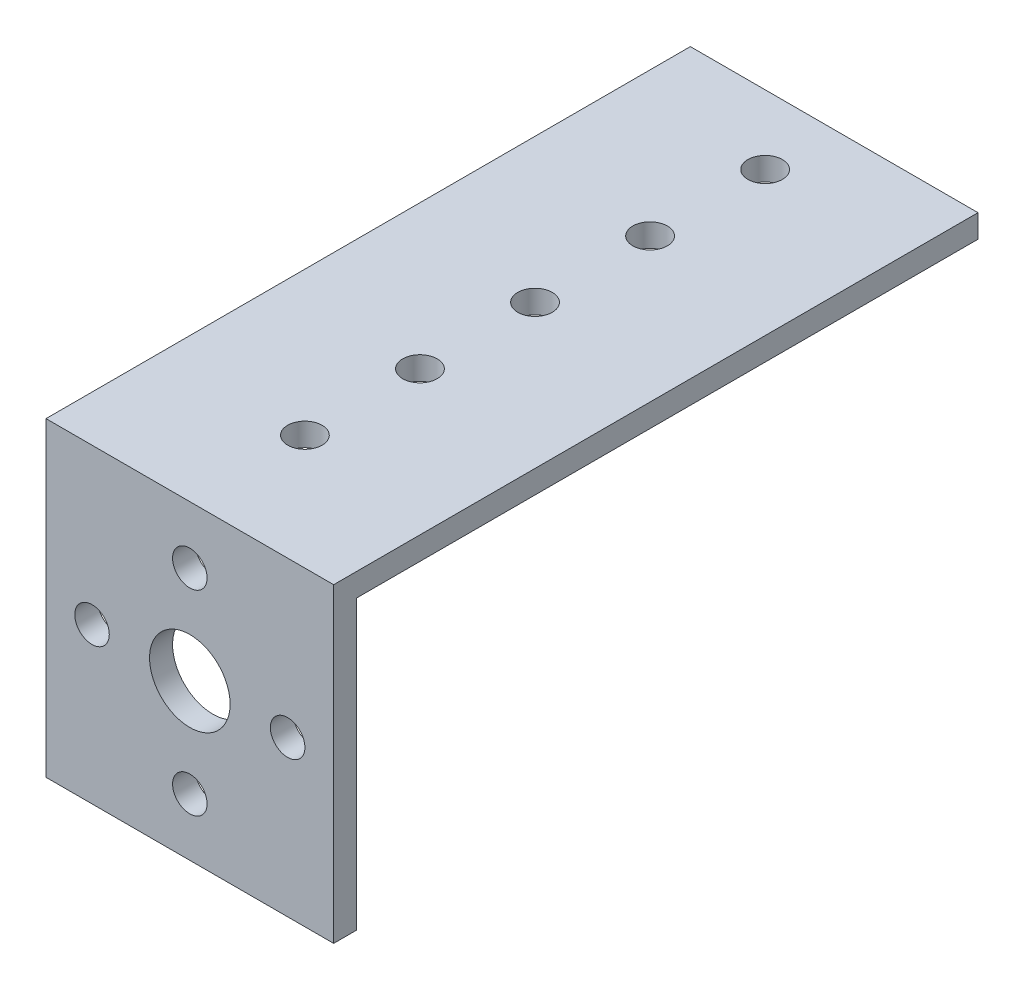
SolidWorks part; units mm, degrees
ref_plane "Front Plane" through (0, 0, 0) normal (0, 0, 1) x (1, 0, 0)
ref_plane "Top Plane" through (0, 0, 0) normal (0, 1, 0) x (1, 0, 0)
ref_plane "Right Plane" through (0, 0, 0) normal (1, 0, 0) x (0, 0, -1)
sketch "Sketch1" plane through (0, 0, 0) normal (1, 0, 0) x (0, 0, -1)
  line L0 (0, 0) -> (0, 27)
  line L1 (0, 27) -> (56, 27)
  line L2 (56, 27) -> (56, 25)
  line L3 (56, 25) -> (2, 25)
  line L4 (2, 25) -> (2, 0)
  line L5 (2, 0) -> (0, 0)
  dimension "D1" = 25
  dimension "D2" = 2
  dimension "D3" = 54
extrude "Boss-Extrude1" add sketch "Sketch1" along normal blind 25
sketch "Sketch2" plane through (0, 0, 0) normal (0, 0, 1) x (1, 0, 0)
  line L0 (12.5, 27) -> (12.5, 0) construction
  line L1 (25, 13.5) -> (0, 13.5) construction
  line L4 (0, 27) -> (0, 0)
  line L5 (0, 0) -> (25, 0)
  line L6 (25, 0) -> (25, 27)
  line L7 (25, 27) -> (0, 27)
  line L8 (0, 27) -> (0, 0) construction
  line L9 (0, 0) -> (25, 0) construction
  line L10 (25, 0) -> (25, 27) construction
  line L11 (25, 27) -> (0, 27) construction
  circle A3 centre (4, 13.5) radius 1.5
  circle A4 centre (12.5, 13.5) radius 3.5
  circle A5 centre (12.5, 22) radius 1.5
  circle A6 centre (21, 13.5) radius 1.5
  circle A7 centre (12.5, 5) radius 1.5
  point P21 (12.5, 13.5)
  dimension "D2" = 3
  dimension "D3" = 7
  dimension "D4" = 8.5
  dimension "D1" = 0
  dimension "D5" = 4
extrude "Cut-Extrude1" cut sketch "Sketch2" against normal blind 25
sketch "Sketch3" plane through (0, 27, 0) normal (0, 1, 0) x (1, 0, 0)
  line L0 (12.5, 0) -> (12.5, 56) construction
  line L1 (25, 0) -> (0, 0) construction
  line L2 (25, 56) -> (0, 56) construction
  circle A0 centre (12.5, 10) radius 1.5
  circle A1 centre (12.5, 20) radius 1.5
  circle A2 centre (12.5, 30) radius 1.5
  circle A3 centre (12.5, 40) radius 1.5
  circle A4 centre (12.5, 50) radius 1.5
  dimension "D1" = 3
  dimension "D3" = 10
  dimension "D4" = 10
  dimension "D2" = 5
extrude "Cut-Extrude2" cut sketch "Sketch3" against normal blind 25
